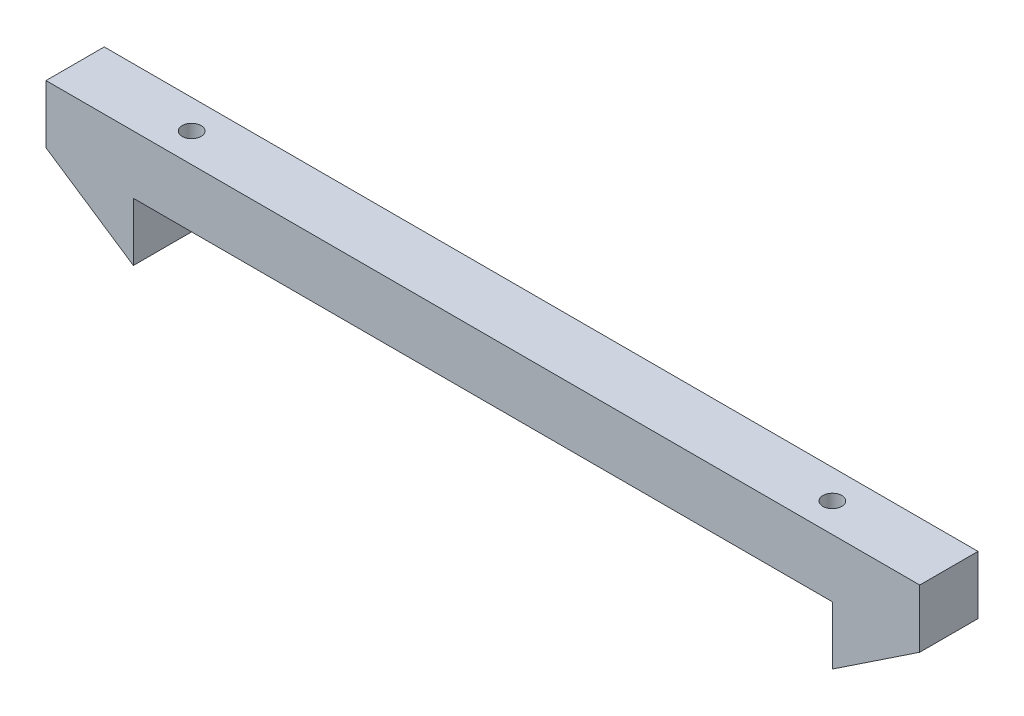
SolidWorks part; units mm, degrees
ref_plane "Front Plane" through (0, 0, 0) normal (1, 0, 0) x (0, 1, 0)
ref_plane "Top Plane" through (0, 0, 0) normal (0, 0, 1) x (0, 1, 0)
ref_plane "Right Plane" through (0, 0, 0) normal (0, 1, 0) x (-1, 0, 0)
sketch "Sketch1" plane through (0, 0, 0) normal (0, 0, 1) x (0, 1, 0)
  line L0 (0, 48) -> (0, -48)
  line L1 (0, -48) -> (-8, -48)
  line L2 (-8, -48) -> (0, -60)
  line L3 (0, -60) -> (8, -60)
  line L4 (8, -60) -> (8, 60)
  line L7 (8, 60) -> (0, 60)
  line L8 (0, 60) -> (-8, 48)
  line L9 (-8, 48) -> (0, 48)
  point P9 (0, 0)
  point P13 (8, 0)
  dimension "D1" = 96
  dimension "D2" = 120
  dimension "D3" = 8
  dimension "D5" = 8
extrude "Boss-Extrude1" add sketch "Sketch1" along normal blind 8
sketch "Sketch2" plane through (0, 0, 0) normal (0, -1, 0) x (1, 0, 0)
  line L0 (0, 0) -> (0, 8) construction
  line L1 (-48, 0) -> (48, 0) construction
  line L2 (-48, 8) -> (48, 8) construction
  line L3 (-48, 8) -> (-48, 0) construction
  circle A0 centre (-44, 4) radius 1.3
  circle A1 centre (44, 4) radius 1.3
  point P10 (0, 4)
  dimension "D1" = 2.6
  dimension "D2" = 4
extrude "Cut-Extrude1" cut sketch "Sketch2" against normal up to next
